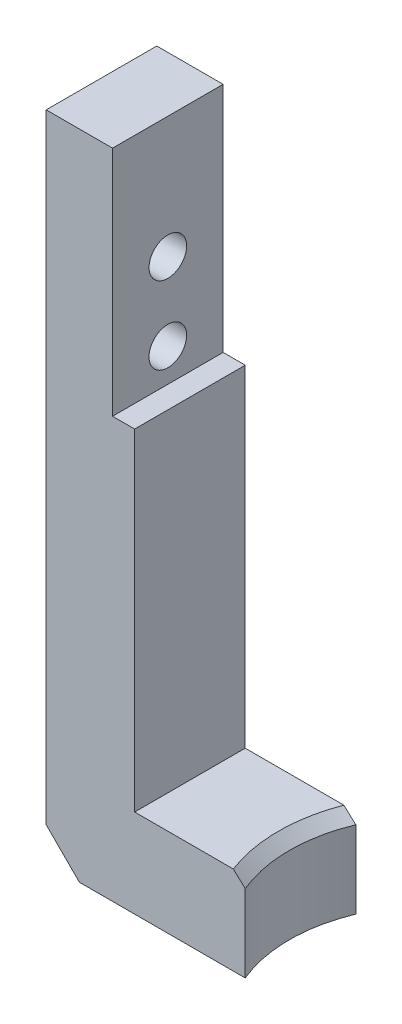
SolidWorks part; units mm, degrees
ref_plane "Plan de face" through (0, 0, 0) normal (0, 0, 1) x (1, 0, 0)
ref_plane "Plan de dessus" through (0, 0, 0) normal (0, 1, 0) x (1, 0, 0)
ref_plane "Plan de droite" through (0, 0, 0) normal (1, 0, 0) x (0, 0, -1)
sketch "Esquisse1" plane through (0, 0, 0) normal (0, 0, 1) x (1, 0, 0)
  line L1 (8, 0) -> (20, 0)
  line L2 (0, 0) -> (0, -8)
  line L3 (0, -8) -> (20, -8)
  line L4 (20, 0) -> (20, -8)
  line L6 (0, 0) -> (0, 30)
  line L7 (6, 30) -> (8, 30)
  line L8 (8, 0) -> (8, 30)
  line L10 (0, 30) -> (0, 51)
  line L11 (0, 51) -> (6, 51)
  line L12 (6, 30) -> (6, 51)
  dimension "D1" = 20
  dimension "D2" = 8
  dimension "D3" = 12
  dimension "D4" = 30
  dimension "D5" = 2
  dimension "D6" = 21
extrude "Boss.-Extru.1" add sketch "Esquisse1" along normal mid plane 10
sketch "Esquisse2" plane through (0, -8, 0) normal (0, -1, 0) x (1, 0, 0)
  line L0 (11, 0) -> (-11, 0) construction
  line L1 (0, 0) -> (30, 0) construction
  circle A0 centre (30, 0) radius 13
  dimension "D2" = 26
  dimension "D1" = 30
extrude "Enlèv. mat.-Extru.1" cut sketch "Esquisse2" against normal blind 10
chamfer "Chanfrein1" distance 3 angle 45 1 edges at (0, -8, 0)
chamfer "Chanfrein2" distance 1 angle 45 1 edges at (17, 0, 0)
hole_wizard "Chambrage pour vis à six pans creux M31" positions "Esquisse7" profile "Esquisse8" counterbore size "M3" standard "ISO" end condition through all
sketch "Esquisse7" plane through (0, 0, 0) normal (-1, 0, 0) x (0, 0, 1)
  line L0 (0, -9.9) -> (0, 9.9) construction
  line L1 (-5, 30) -> (5, 30) construction
  point P0 (0, 40)
  point P4 (0, 33)
  dimension "D1" = 7
  dimension "D2" = 3
sketch "Esquisse8" plane through (0, 40, 0) normal (0, 1, 0) x (0, 0, 1)
  line L0 (0, 0) -> (0, 18)
  line L1 (0, 18) -> (1.7, 18)
  line L3 (1.7, 18) -> (1.7, 3.4)
  line L4 (1.7, 3.4) -> (3.25, 3.4)
  line L5 (3.25, 3.4) -> (3.25, 0)
  line L7 (3.25, 0) -> (0, 0)
  line L11 (0, -6.35) -> (0, 107.95) construction
  dimension "Diamètre du perçage jusqu'au prochain" = 3.4
  dimension "Profondeur du perçage jusqu'au prochain" = 18
  dimension "Diamètre du chambrage" = 6.5
  dimension "Profondeur du chambrage" = 3.4
